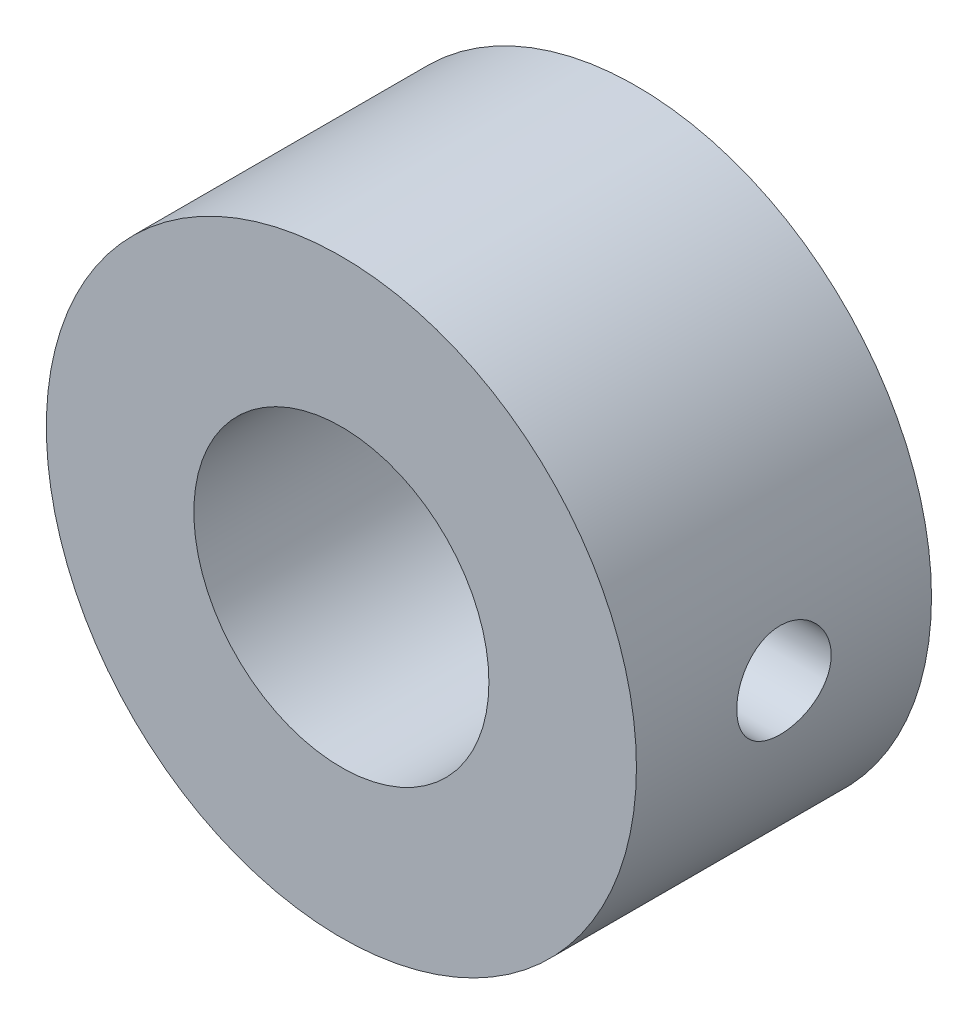
SolidWorks part; units mm, degrees
ref_plane "Front Plane" through (0, 0, 0) normal (0, 0, 1) x (1, 0, 0)
ref_plane "Top Plane" through (0, 0, 0) normal (0, 1, 0) x (1, 0, 0)
ref_plane "Right Plane" through (0, 0, 0) normal (1, 0, 0) x (0, 0, -1)
sketch "Sketch1" plane through (0, 0, 0) normal (0, 0, 1) x (1, 0, 0)
  circle A0 centre (0, 0) radius 5
  circle A1 centre (0, 0) radius 2.5
  dimension "D1" = 5
  dimension "D2" = 10
extrude "Boss-Extrude1" add sketch "Sketch1" along normal mid plane 5
hole_wizard "M2x0.4 Tapped Hole1" positions "Sketch3" profile "Sketch2" tap size "M2x0.4" standard "ANSI Metric"
sketch "Sketch3" plane through (0, 0, 0) normal (1, 0, 0) x (0, 0, -1)
  point P0 (0, 0)
sketch "Sketch2" plane through (0, 0, 0) normal (0, 1, 0) x (0, 0, 1)
  line L0 (0, 0) -> (0, 5)
  line L1 (0, 5) -> (0.8, 5)
  line L2 (0.8, 5) -> (0.8, 0)
  line L5 (0.8, 0) -> (0, 0)
  line L11 (0, -6.35) -> (0, 107.95) construction
  dimension "Thread Major Dia." = 1.6
  dimension "Thru Tap Drill Depth" = 5
